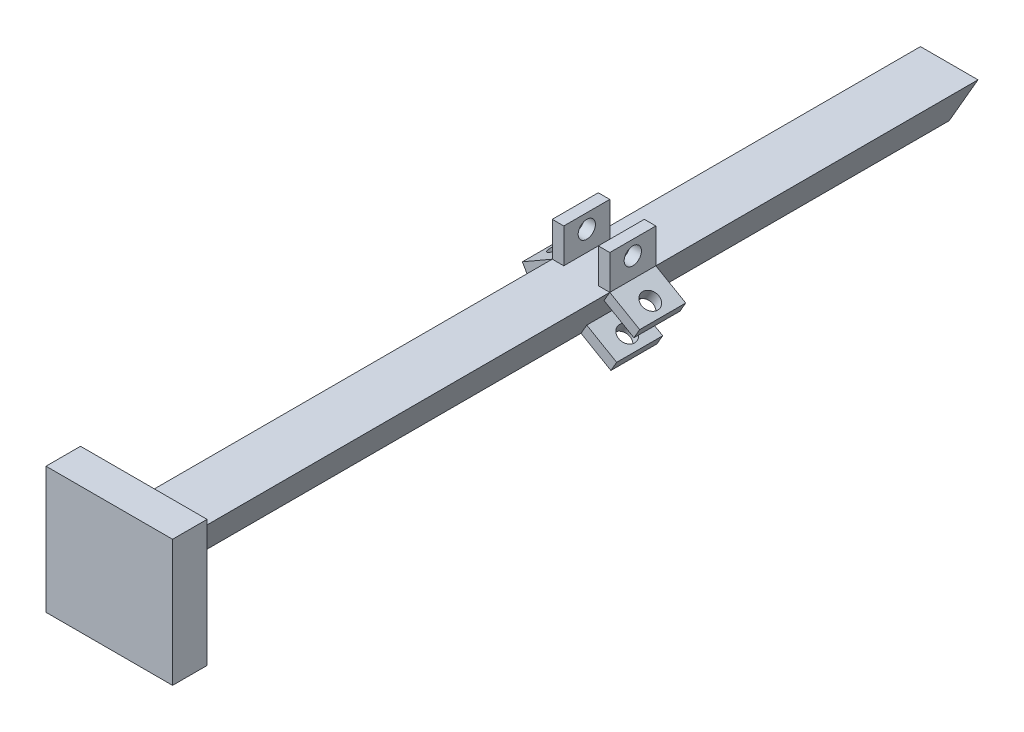
SolidWorks part; units mm, degrees
ref_plane "Plan de face" through (0, 0, 0) normal (0, 0, 1) x (1, 0, 0)
ref_plane "Plan de dessus" through (0, 0, 0) normal (0, 1, 0) x (1, 0, 0)
ref_plane "Plan de droite" through (0, 0, 0) normal (1, 0, 0) x (0, 0, -1)
sketch "Esquisse1" plane through (0, 0, 0) normal (0, 0, 1) x (1, 0, 0)
  line L0 (-1.4021, 1.2008) -> (3.5979, 1.2008) construction
  line L1 (3.5979, 1.2008) -> (1.0953, -3.1308) construction
  line L2 (1.0953, -3.1308) -> (-1.4021, 1.2008) construction
  line L3 (-1.4021, 1.2008) -> (1.0953, -3.1308)
  line L4 (1.0953, -3.1308) -> (3.5979, 1.2008)
  line L5 (3.5979, 1.2008) -> (-1.4021, 1.2008)
extrude "Boss.-Extru.1" add sketch "Esquisse1" along normal blind 70 contours L5 L3 L4
sketch "Esquisse3" plane through (0, 1.2008, 0) normal (0, 1, 0) x (1, 0, 0)
  line L0 (-1.4021, -28) -> (-0.4021, -28)
  line L1 (-1.4021, -28) -> (-1.4021, -32)
  line L2 (-0.4021, -28) -> (-0.4021, -32)
  line L3 (-1.4021, -32) -> (-0.4021, -32)
  line L4 (-1.4021, -70) -> (-1.4021, 0) construction
  dimension "D1" = 32
  dimension "D2" = 4
extrude "Boss.-Extru.2" add sketch "Esquisse3" along normal blind 3
sketch "Esquisse4" plane through (0, 1.2008, 0) normal (0, 1, 0) x (1, 0, 0)
  line L0 (2.5979, -28) -> (3.5979, -28)
  line L1 (2.5979, -28) -> (2.5979, -32)
  line L2 (3.5979, -28) -> (3.5979, -32)
  line L3 (2.5979, -32) -> (3.5979, -32)
  line L4 (3.5979, -70) -> (3.5979, 0) construction
  line L5 (-0.4021, -28) -> (-1.4021, -28) construction
  line L6 (-1.4021, -32) -> (-0.4021, -32) construction
  dimension "D1" = 1
extrude "Boss.-Extru.3" add sketch "Esquisse4" along normal blind 3
sketch "Esquisse6" plane through (3.5979, 0, 0) normal (1, 0, 0) x (0, 0, -1)
  circle A0 centre (-30, 2.9508) radius 0.75
  dimension "D1" = 2
  dimension "D2" = 1.25
extrude "Enlèv. mat.-Extru.1" cut sketch "Esquisse6" against normal blind 5
sketch "Esquisse7" plane through (2.1773, -1.2579, 0) normal (0.8659, -0.5003, 0) x (0, 0, -1)
  line L0 (-27.9999, 2.8396) -> (-27.9999, 1.8396)
  line L1 (-27.9999, 2.8396) -> (-31.9999, 2.8396)
  line L2 (-27.9999, 1.8396) -> (-31.9999, 1.8396)
  line L3 (-31.9999, 2.8396) -> (-31.9999, 1.8396)
  line L6 (-32, 2.8396) -> (-28, 2.8396) construction
extrude "Boss.-Extru.4" add sketch "Esquisse7" along normal blind 3
sketch "Esquisse8" plane through (2.1773, -1.2579, 0) normal (0.8659, -0.5003, 0) x (0, 0, -1)
  line L0 (-27.9999, -1.1629) -> (-27.9999, -2.1629)
  line L1 (-27.9999, -1.1629) -> (-31.9999, -1.1629)
  line L2 (-27.9999, -2.1629) -> (-31.9999, -2.1629)
  line L3 (-31.9999, -1.1629) -> (-31.9999, -2.1629)
  line L4 (-70, -2.1629) -> (0, -2.1629) construction
  line L5 (-27.9999, 1.8396) -> (-27.9999, 2.8396) construction
  dimension "D1" = 1
  dimension "D2" = 4
extrude "Boss.-Extru.5" add sketch "Esquisse8" along normal blind 3
sketch "Esquisse9" plane through (-1.082, -1.8728, 0) normal (-0.5003, -0.8659, 0) x (-0.8659, 0.5003, 0)
  line L0 (-5.5146, -31.9999) -> (-5.5146, -27.9999) construction
  circle A0 centre (-4.2646, -29.9999) radius 0.75
  dimension "D1" = 2
  dimension "D2" = 1.25
extrude "Enlèv. mat.-Extru.2" cut sketch "Esquisse9" against normal blind 5.1
sketch "Esquisse10" plane through (-0.5327, -0.3071, 0) normal (-0.8663, -0.4995, 0) x (0, 0, 1)
  line L0 (27.9999, -3.2593) -> (27.9999, -2.2593)
  line L1 (27.9999, -3.2593) -> (31.9999, -3.2593)
  line L2 (27.9999, -2.2593) -> (31.9999, -2.2593)
  line L3 (31.9999, -3.2593) -> (31.9999, -2.2593)
  line L4 (31.9999, -3.2593) -> (27.9999, -3.2593) construction
  line L5 (27.9999, -3.2593) -> (27.9999, -2.7591) construction
  dimension "D1" = 1
  dimension "D2" = 4
extrude "Boss.-Extru.6" add sketch "Esquisse10" along normal blind 3
sketch "Esquisse11" plane through (-0.5327, -0.3071, 0) normal (-0.8663, -0.4995, 0) x (0, 0, 1)
  line L0 (28, 0.7407) -> (28, 1.7407)
  line L1 (28, 0.7407) -> (32, 0.7407)
  line L2 (28, 1.7407) -> (32, 1.7407)
  line L3 (32, 0.7407) -> (32, 1.7407)
  line L4 (28, 1.2412) -> (28, 1.7407) construction
  line L5 (28, 1.7407) -> (32, 1.7407) construction
  dimension "D1" = 1
  dimension "D2" = 4
extrude "Boss.-Extru.7" add sketch "Esquisse11" along normal blind 3
sketch "Esquisse12" plane through (-0.8694, 1.508, 0) normal (-0.4995, 0.8663, 0) x (0.8663, 0.4995, 0)
  circle A0 centre (-2.3649, -30) radius 0.75
  dimension "D1" = 1.25
  dimension "D2" = 2
extrude "Enlèv. mat.-Extru.3" cut sketch "Esquisse12" against normal blind 5.1
sketch "Esquisse13" plane through (0, 0, 70) normal (0, 0, 1) x (1, 0, 0)
  line L1 (-4.4021, -6.3808) -> (6.5979, -6.3808)
  line L2 (-4.4021, -6.3808) -> (-4.4021, 4.6192)
  line L3 (-4.4021, 4.6192) -> (6.5979, 4.6192)
  line L4 (6.5979, -6.3808) -> (6.5979, 4.6192)
  line L5 (-4.4021, -6.3808) -> (6.5979, 4.6192) construction
  line L6 (-4.4021, 4.6192) -> (6.5979, -6.3808) construction
  point P0 (1.0979, -0.8808)
  dimension "D1" = 2.25
  dimension "D2" = 2.5
  dimension "D3" = 11
extrude "Boss.-Extru.8" add sketch "Esquisse13" along normal blind 3
